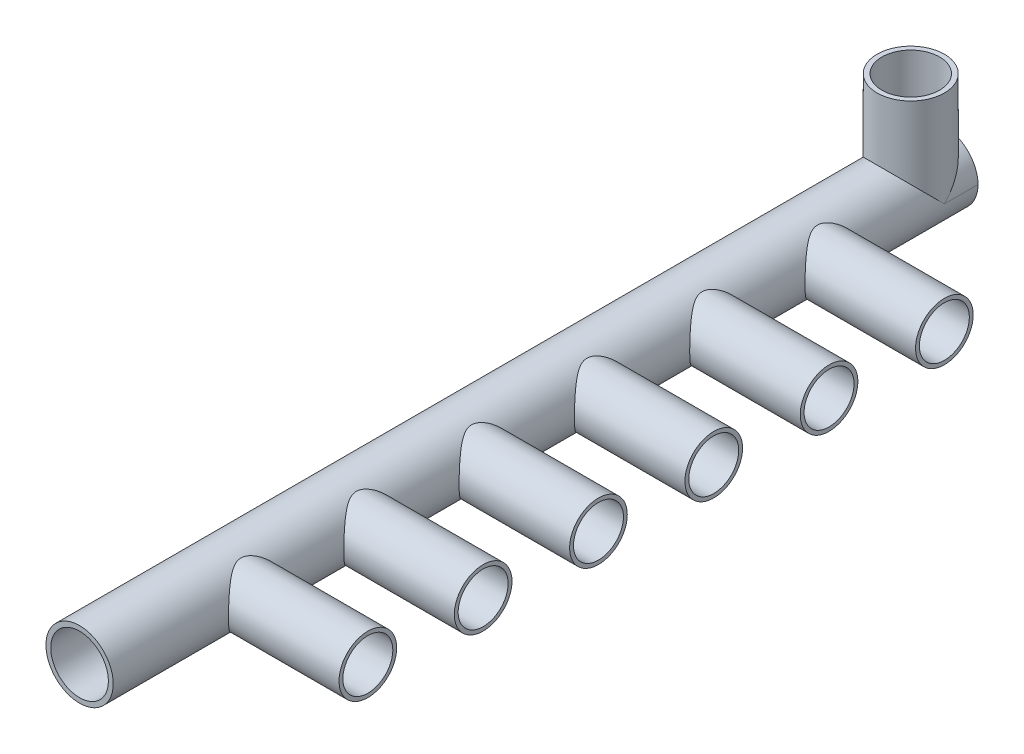
SolidWorks part; units mm, degrees
ref_plane "Front Plane" through (0, 0, 0) normal (0, 0, 1) x (1, 0, 0)
ref_plane "Top Plane" through (0, 0, 0) normal (0, 1, 0) x (1, 0, 0)
ref_plane "Right Plane" through (0, 0, 0) normal (1, 0, 0) x (0, 0, -1)
sketch "Sketch1" plane through (0, 0, 0) normal (0, 0, 1) x (1, 0, 0)
  circle A0 centre (0, 0) radius 35
extrude "Boss-Extrude1" add sketch "Sketch1" along normal blind 900
sketch "Sketch2" plane through (0, 0, 0) normal (1, 0, 0) x (0, 0, -1)
  line L0 (-900, 35) -> (-900, -35) construction
  circle A0 centre (-750, 0) radius 30
  circle A1 centre (-750, 0) radius 26
  circle A2 centre (-630, 0) radius 26
  circle A3 centre (-630, 0) radius 30
  circle A4 centre (-510, 0) radius 26
  circle A5 centre (-510, 0) radius 30
  circle A6 centre (-390, 0) radius 26
  circle A7 centre (-390, 0) radius 30
  circle A8 centre (-270, 0) radius 26
  circle A9 centre (-270, 0) radius 30
  circle A10 centre (-150, 0) radius 26
  circle A11 centre (-150, 0) radius 30
  dimension "D1" = 60
  dimension "D2" = 6
  dimension "75" = 150
extrude "Boss-Extrude2" add sketch "Sketch2" along normal blind 150
sketch "Sketch4" plane through (0, 0, 0) normal (1, 0, 0) x (0, 0, -1)
  circle A0 centre (-750, 0) radius 26
  circle A1 centre (-630, 0) radius 26
  circle A2 centre (-510, 0) radius 26
  circle A3 centre (-390, 0) radius 26
  circle A4 centre (-270, 0) radius 26
  circle A5 centre (-150, 0) radius 26
extrude "Cut-Extrude2" cut sketch "Sketch4" along normal blind 200
sketch "Sketch5" plane through (0, 0, 0) normal (0, 1, 0) x (1, 0, 0)
  circle A0 centre (0, -35) radius 35
  circle A1 centre (0, -35) radius 28
  dimension "35" = 35
extrude "Boss-Extrude3" add sketch "Sketch5" along normal blind 100
sketch "Sketch6" plane through (0, 0, 900) normal (0, 0, 1) x (1, 0, 0)
  circle A0 centre (0, 0) radius 30
extrude "Cut-Extrude3" cut sketch "Sketch6" against normal blind 895
sketch "Sketch7" plane through (0, 100, 0) normal (0, 1, 0) x (1, 0, 0)
  circle A0 centre (0, -35) radius 30
extrude "Cut-Extrude4" cut sketch "Sketch7" against normal blind 104
